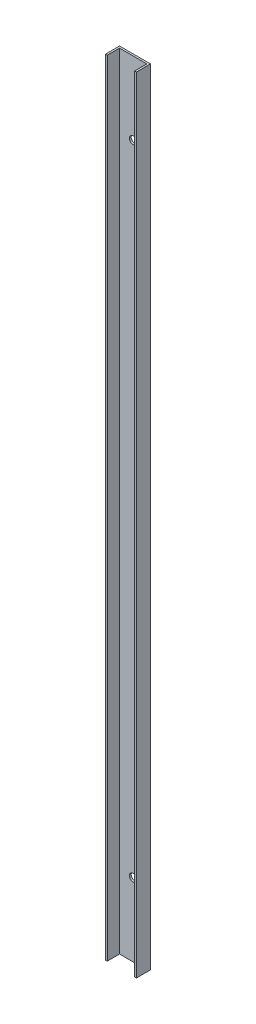
SolidWorks part; units mm, degrees
ref_plane "Front Plane" through (0, 0, 0) normal (0, 0, 1) x (1, 0, 0)
ref_plane "Top Plane" through (0, 0, 0) normal (0, 1, 0) x (1, 0, 0)
ref_plane "Right Plane" through (0, 0, 0) normal (1, 0, 0) x (0, 0, -1)
sketch "Sketch1" plane through (0, 0, 0) normal (0, 1, 0) x (1, 0, 0)
  line L0 (-10.9455, 0) -> (-10.9455, 7.7)
  line L1 (-10.9455, 7.7) -> (6.0545, 7.7)
  line L2 (6.0545, 7.7) -> (6.0545, 0)
  dimension "D1" = 7.7
  dimension "D2" = 17
extrude "Extrude-Thin1" add sketch "Sketch1" along normal blind 430 thin
sketch "Sketch2" plane through (0, 0, -6.7) normal (0, 0, 1) x (1, 0, 0)
  line L0 (6.0545, 430) -> (6.0545, 0) construction
  line L1 (-9.9455, 430) -> (5.0545, 430) construction
  line L2 (80.2435, 215) -> (-35.0705, 215) construction
  line L3 (-9.9455, 0) -> (5.0545, 0) construction
  circle A0 centre (-2.4455, 390) radius 2.1
  circle A1 centre (-2.4455, 40) radius 2.1
  dimension "D3" = 4.2
  dimension "D1" = 8.5
  dimension "D2" = 40
  dimension "D4" = 215
extrude "Cut-Extrude1" cut sketch "Sketch2" against normal blind 10
